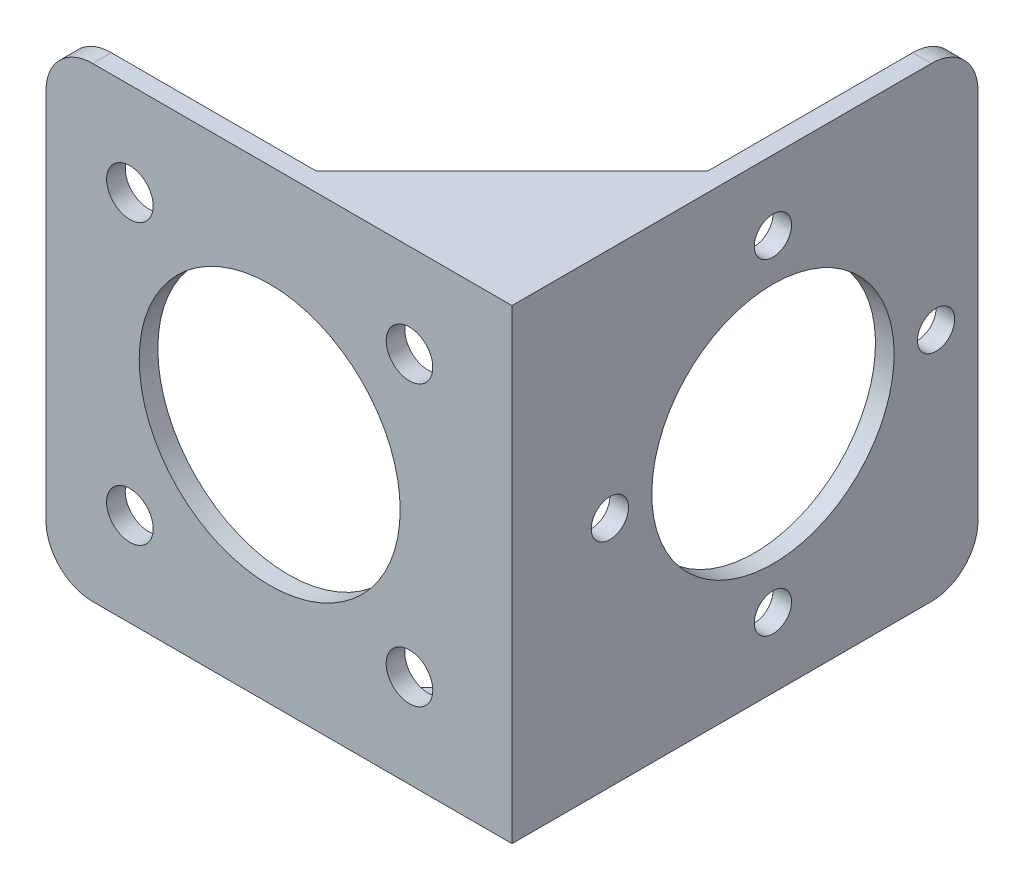
SolidWorks part; units mm, degrees
material "AISI 304"
ref_plane "前视基准面" through (0, 0, 0) normal (0, 0, 1) x (1, 0, 0)
ref_plane "上视基准面" through (0, 0, 0) normal (0, 1, 0) x (1, 0, 0)
ref_plane "右视基准面" through (0, 0, 0) normal (1, 0, 0) x (0, 0, -1)
sketch "草图1" plane through (0, 0, 0) normal (0, 0, 1) x (1, 0, 0)
  line L1 (-25, 25) -> (25, 25)
  line L2 (-25, 25) -> (-25, -25)
  line L3 (-25, -25) -> (25, -25)
  line L4 (25, 25) -> (25, -25)
  line L5 (-25, 25) -> (25, -25) construction
  line L6 (-25, -25) -> (25, 25) construction
  line L9 (55, 0) -> (-55, 0) construction
  circle A0 centre (-1, 0) radius 14
  circle A1 centre (-16, 15) radius 2.5
  circle A2 centre (-16, -15) radius 2.5
  circle A3 centre (14, -15) radius 2.5
  circle A4 centre (14, 15) radius 2.5
  point P0 (0, 0)
  dimension "D3" = 5
  dimension "D1" = 50
  dimension "D2" = 50
extrude "凸台-拉伸1" add sketch "草图1" along normal blind 2
sketch "草图3" plane through (0, 0, 0) normal (0, 0, -1) x (-1, 0, 0)
  line L0 (25, -25) -> (-25, -25) construction
  line L1 (-25, 25) -> (-23, 25)
  line L2 (-25, 25) -> (-25, -25)
  line L3 (-25, -25) -> (-23, -25)
  line L4 (-23, 25) -> (-23, -25)
  dimension "D1" = 2
extrude "凸台-拉伸3" add sketch "草图3" along normal blind 48
sketch "草图4" plane through (0, 25, 0) normal (0, 1, 0) x (1, 0, 0)
  line L0 (0, -2) -> (25, 23)
  line L1 (25, -2) -> (-25, -2) construction
  line L2 (25, -2) -> (25, 48) construction
  line L3 (25, 23) -> (25, -2)
  line L4 (25, -2) -> (0, -2)
extrude "凸台-拉伸4" add sketch "草图4" against normal blind 2
sketch "草图5" plane through (0, -25, 0) normal (0, -1, 0) x (1, 0, 0)
  line L0 (25, 2) -> (0, 2)
  line L1 (-25, 2) -> (25, 2) construction
  line L2 (0, 2) -> (25, -23)
  line L3 (25, 2) -> (25, -48) construction
  line L4 (25, -23) -> (25, 2)
extrude "凸台-拉伸5" add sketch "草图5" against normal blind 2
sketch "草图6" plane through (25, 0, 0) normal (1, 0, 0) x (0, 0, -1)
  line L1 (55, 0) -> (-55, 0) construction
  circle A0 centre (26, 0) radius 13
  circle A1 centre (43.5, 0) radius 2
  circle A2 centre (26, 17.5) radius 2
  circle A3 centre (26, -17.5) radius 2
  circle A4 centre (8.5, 0) radius 2
extrude "切除-拉伸1" cut sketch "草图6" against normal blind 2
fillet "圆角1" radius 5 4 edges at (-25, -25, 1) (-25, 25, 1) (24, 25, -48) (24, -25, -48)
